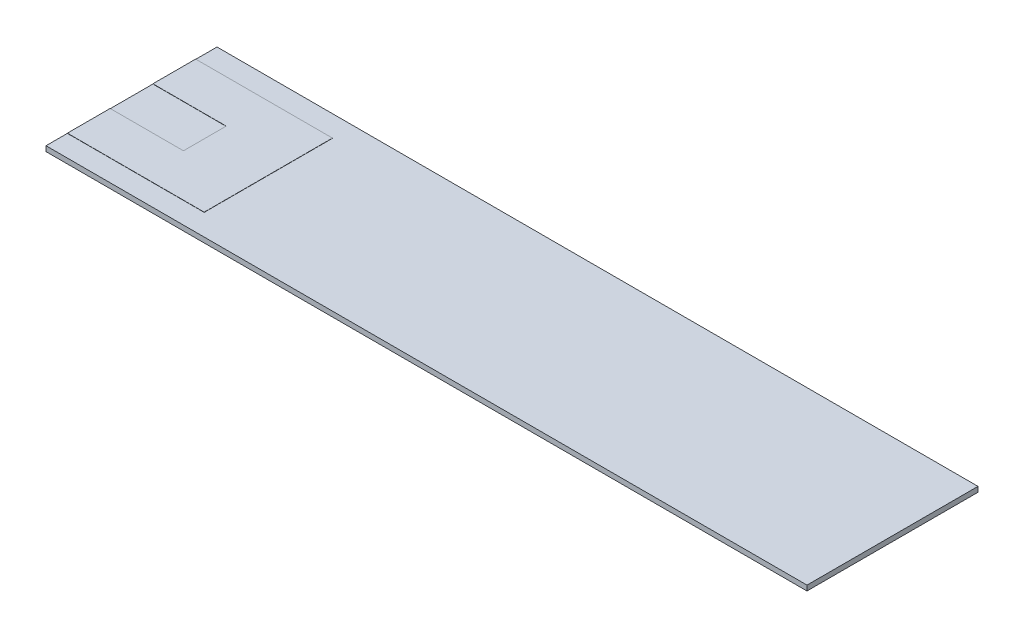
SolidWorks part; units mm, degrees
ref_plane "Front Plane" through (0, 0, 0) normal (0, 0, 1) x (1, 0, 0)
ref_plane "Top Plane" through (0, 0, 0) normal (0, 1, 0) x (1, 0, 0)
ref_plane "Right Plane" through (0, 0, 0) normal (1, 0, 0) x (0, 0, -1)
sketch "Sketch1" plane through (0, 0, 0) normal (0, 1, 0) x (1, 0, 0)
  line L4 (30, -5) -> (74.5, -5)
  line L5 (74.5, 5) -> (74.5, -5)
  line L8 (30, 5) -> (74.5, 5)
  line L10 (0, 0) -> (74.5, 0) construction
  line L11 (30, 5) -> (30, -5)
  dimension "D4" = 10
  dimension "D6" = 44.5
  dimension "D7" = 5
extrude "Boss-Extrude1" add sketch "Sketch1" against normal blind 0.3 and the other way blind 0.0001
sketch "Sketch2" plane through (0, 0.0001, 0) normal (0, 1, 0) x (1, 0, 0)
  line L2 (30, 3.75) -> (38, 3.75)
  line L3 (38, 3.75) -> (38, -3.75)
  line L4 (38, -3.75) -> (30, -3.75)
  line L6 (30, -1.25) -> (34.2883, -1.25)
  line L7 (34.2883, -1.25) -> (34.2883, 1.25)
  line L8 (34.2883, 1.25) -> (30, 1.25)
  line L10 (30, -5) -> (74.5, -5) construction
  line L11 (30, 3.75) -> (30, 1.25)
  line L12 (30, -1.25) -> (30, -3.75)
  dimension "D1" = 7.5
  dimension "D2" = 2.5
  dimension "D3" = 2.5
  dimension "D4" = 8
  dimension "D7" = 1.25
extrude "Boss-Extrude3" add sketch "Sketch2" along normal blind 0.0126
